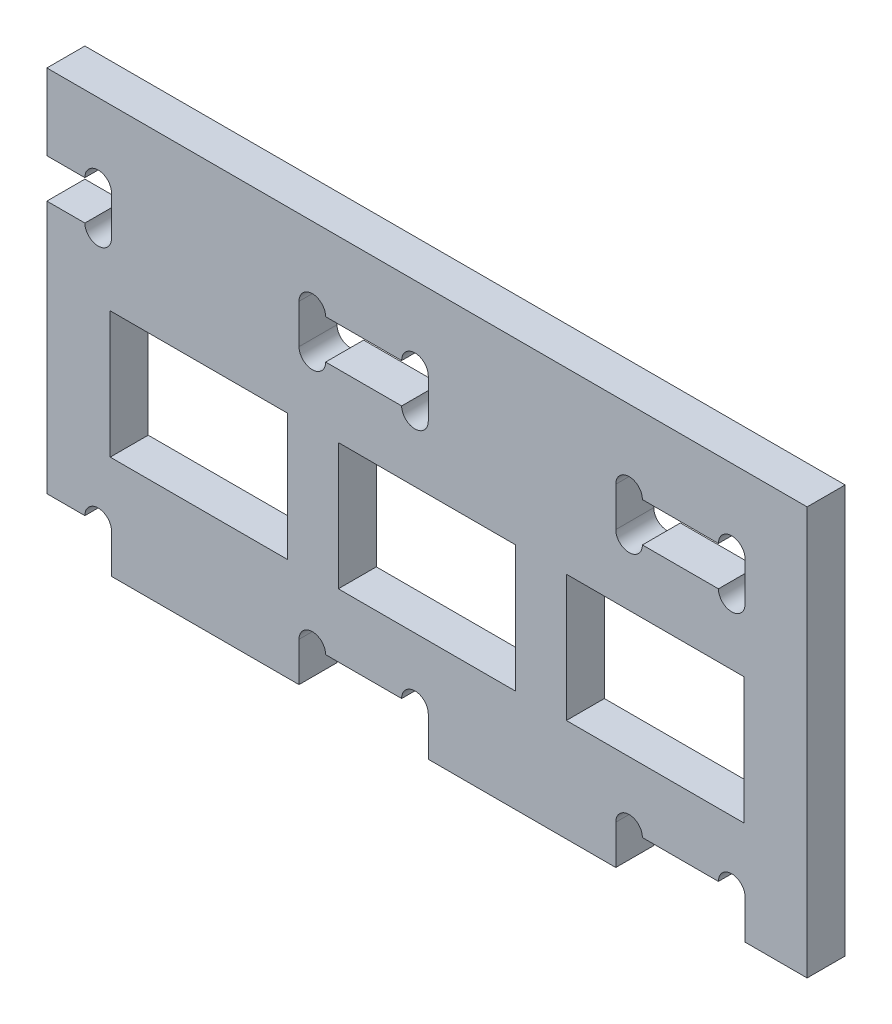
SolidWorks part; units mm, degrees
material "环氧树脂板"
ref_plane "前视基准面" through (0, 0, 0) normal (0, 0, 1) x (1, 0, 0)
ref_plane "上视基准面" through (0, 0, 0) normal (0, 1, 0) x (1, 0, 0)
ref_plane "右视基准面" through (0, 0, 0) normal (1, 0, 0) x (0, 0, -1)
sketch "草图1" plane through (0, 0, 0) normal (0, 0, 1) x (1, 0, 0)
  line L0 (-5.1, -16.1) -> (-19.9, -16.1)
  line L1 (35, -16.1) -> (30.1, -16.1)
  line L2 (35, -16.1) -> (35, 16.1)
  line L3 (35, 16.1) -> (-35, 16.1)
  line L4 (-35, -16.1) -> (-35, 16.1)
  line L5 (35, -16.1) -> (-35, 16.1) construction
  line L6 (35, 16.1) -> (-35, -16.1) construction
  line L7 (5.1, -16.1) -> (-5.1, -16.1) construction
  line L8 (5.1, -16.1) -> (5.1, -13)
  line L9 (5.1, -13) -> (-5.1, -13)
  line L10 (-5.1, -16.1) -> (-5.1, -13)
  line L11 (5.1, -16.1) -> (-5.1, -13) construction
  line L12 (5.1, -13) -> (-5.1, -16.1) construction
  line L13 (5.1, 7) -> (-5.1, 7)
  line L14 (5.1, 7) -> (5.1, 10.1)
  line L15 (5.1, 10.1) -> (-5.1, 10.1)
  line L16 (-5.1, 7) -> (-5.1, 10.1)
  line L17 (5.1, 7) -> (-5.1, 10.1) construction
  line L18 (5.1, 10.1) -> (-5.1, 7) construction
  line L19 (-30.1, -16.1) -> (-30.1, -13)
  line L20 (12, -8) -> (-2, -8)
  line L21 (12, -8) -> (12, 2)
  line L22 (12, 2) -> (-2, 2)
  line L23 (-2, -8) -> (-2, 2)
  line L24 (12, -8) -> (-2, 2) construction
  line L25 (12, 2) -> (-2, -8) construction
  line L26 (-19.9, 7) -> (-30.1, 7)
  line L27 (-19.9, 7) -> (-19.9, 10.1)
  line L28 (-19.9, 10.1) -> (-30.1, 10.1)
  line L29 (-30.1, 7) -> (-30.1, 10.1)
  line L30 (-19.9, 7) -> (-30.1, 10.1) construction
  line L31 (-19.9, 10.1) -> (-30.1, 7) construction
  line L32 (-30.1, -13) -> (-19.9, -13)
  line L33 (-19.9, -13) -> (-19.9, -16.1)
  line L34 (0, -14.55) -> (0, -21.8655) construction
  line L35 (19.9, 10.1) -> (30.1, 7) construction
  line L36 (19.9, 7) -> (30.1, 10.1) construction
  line L37 (19.9, -13) -> (19.9, -16.1)
  line L38 (30.1, -13) -> (19.9, -13)
  line L39 (30.1, 7) -> (30.1, 10.1)
  line L40 (19.9, 10.1) -> (30.1, 10.1)
  line L41 (19.9, 7) -> (19.9, 10.1)
  line L42 (19.9, 7) -> (30.1, 7)
  line L43 (30.1, -16.1) -> (30.1, -13)
  line L44 (-30.1, -16.1) -> (-35, -16.1)
  line L45 (19.9, -16.1) -> (5.1, -16.1)
  line L47 (-6, -8) -> (-20, -8)
  line L48 (-6, -8) -> (-6, 2)
  line L49 (-6, 2) -> (-20, 2)
  line L50 (-20, -8) -> (-20, 2)
  line L51 (-6, -8) -> (-20, 2) construction
  line L52 (-6, 2) -> (-20, -8) construction
  line L53 (30, -8) -> (16, -8)
  line L54 (30, -8) -> (30, 2)
  line L55 (30, 2) -> (16, 2)
  line L56 (16, -8) -> (16, 2)
  line L57 (30, -8) -> (16, 2) construction
  line L58 (30, 2) -> (16, -8) construction
  circle A0 centre (-4.05, 10.1) radius 1.05
  circle A1 centre (4.05, 10.1) radius 1.05
  circle A2 centre (-4.05, 7) radius 1.05
  circle A3 centre (4.05, 7) radius 1.05
  circle A4 centre (-4.05, -13) radius 1.05
  circle A5 centre (4.05, -13) radius 1.05
  circle A6 centre (-29.05, -13) radius 1.05
  circle A7 centre (-20.95, -13) radius 1.05
  circle A8 centre (-29.05, 10.1) radius 1.05
  circle A9 centre (-20.95, 10.1) radius 1.05
  circle A10 centre (-20.95, 7) radius 1.05
  circle A11 centre (-29.05, 7) radius 1.05
  circle A12 centre (29.05, 7) radius 1.05
  circle A13 centre (20.95, 7) radius 1.05
  circle A14 centre (20.95, 10.1) radius 1.05
  circle A15 centre (29.05, 10.1) radius 1.05
  circle A16 centre (20.95, -13) radius 1.05
  circle A17 centre (29.05, -13) radius 1.05
  point P0 (0, 0)
  point P6 (0, -14.55)
  point P11 (0, 8.55)
  point P28 (5, -3)
  point P33 (-25, 8.55)
  point P76 (25, 8.55)
  point P77 (-13, -3)
  point P82 (23, -3)
  dimension "D5" = 2.1
  dimension "D1" = 23.1
  dimension "D2" = 3.1
  dimension "D3" = 10.2
  dimension "D4" = 6
  dimension "D6" = 70
  dimension "D7" = 5
  dimension "D8" = 5
  dimension "D9" = 25
  dimension "D10" = 15
  dimension "D11" = 4
  dimension "D12" = 5
  dimension "D13" = 4
extrude "凸台-拉伸1" add sketch "草图1" along normal blind 3 contours A5 L8 L1 L2 L3 L4 L0 L10 A4 L9 A3 L13 A2 L16 A0 L15 A1 L14 L20 L23 L22 L21
sketch "草图2" plane through (0, 0, 3) normal (0, 0, 1) x (1, 0, 0)
  line L1 (-25, -16.1) -> (-35, -16.1)
  line L2 (-25, -16.1) -> (-25, 16.1)
  line L3 (-25, 16.1) -> (-35, 16.1)
  line L4 (-35, -16.1) -> (-35, 16.1)
  line L5 (-25, -16.1) -> (-35, 16.1) construction
  line L6 (-25, 16.1) -> (-35, -16.1) construction
  point P0 (-30, 0)
  dimension "D1" = 10
extrude "切除-拉伸1" cut sketch "草图2" against normal blind 10
